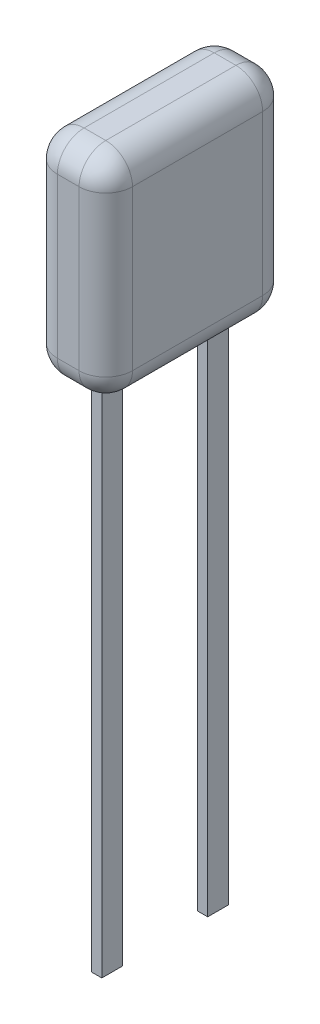
SolidWorks part; units mm, degrees
ref_plane "Front Plane" through (0, 0, 0) normal (0, 0, 1) x (1, 0, 0)
ref_plane "Top Plane" through (0, 0, 0) normal (0, 1, 0) x (1, 0, 0)
ref_plane "Right Plane" through (0, 0, 0) normal (1, 0, 0) x (0, 0, -1)
sketch "Sketch1" plane through (0, 0, 0) normal (1, 0, 0) x (0, 0, -1)
  line L1 (-1.56, 2.55) -> (1.56, 2.55)
  line L2 (-2.2, 1.91) -> (-2.2, -1.91)
  line L3 (-1.56, -2.55) -> (1.56, -2.55)
  line L4 (2.2, 1.91) -> (2.2, -1.91)
  line L5 (-2.2, 2.55) -> (2.2, -2.55) construction
  line L6 (-2.2, -2.55) -> (2.2, 2.55) construction
  arc A0 (-2.2, -1.91) -> (-1.56, -2.55) centre (-1.56, -1.91) ccw
  arc A1 (1.56, -2.55) -> (2.2, -1.91) centre (1.56, -1.91) ccw
  arc A2 (1.56, 2.55) -> (2.2, 1.91) centre (1.56, 1.91) cw
  arc A3 (-1.56, 2.55) -> (-2.2, 1.91) centre (-1.56, 1.91) ccw
  point P0 (0, 0)
  dimension "D3" = 0.64
  dimension "D1" = 4.4
  dimension "D2" = 5.1
extrude "Boss-Extrude1" add sketch "Sketch1" along normal blind 1.8
fillet "Fillet1" radius 0.64 16 edges at (1.8, 2.3625, -2.0125) (1.8, 0, -2.2) (1.8, -2.3625, -2.0125) (1.8, -2.55, 0) (1.8, -2.3625, 2.0125) (1.8, 0, 2.2) (1.8, 2.3625, 2.0125) (0, 2.3625, -2.0125) (0, 0, -2.2) (0, -2.3625, -2.0125) (0, -2.55, 0) (0, -2.3625, 2.0125) (0, 0, 2.2) (0, 2.3625, 2.0125) (1.8, 2.55, 0) (0, 2.55, 0)
ref_plane "Plane1" through (0.9, 0, 0) normal (1, 0, 0) x (0, 0, -1)
sketch "Sketch2" plane through (0.9, 0, 0) normal (1, 0, 0) x (0, 0, -1)
  line L0 (0, 0) -> (0, -3.8385) construction
  line L1 (0, -3.8385) -> (0, -10.741) construction
  line L2 (0, -10.741) -> (-1.2695, -10.741) construction
  line L3 (-1.2695, -10.741) -> (-1.2695, -10.3439) construction
  line L4 (1.0191, -14.926) -> (1.5199, -14.926)
  line L5 (-1.0191, -2.2634) -> (-0.3535, -1.9984)
  line L6 (-0.3535, -1.9984) -> (-0.3535, -1.5016)
  line L7 (-0.3535, -1.5016) -> (-1.5199, -1.5016)
  line L8 (-1.5199, -1.5016) -> (-1.5199, -10.3439)
  line L9 (-1.0191, -2.2634) -> (-1.0191, -14.926)
  line L10 (-1.0191, -14.926) -> (-1.5199, -14.926)
  line L11 (-1.5199, -14.926) -> (-1.5199, -10.3439)
  line L12 (1.5199, -14.926) -> (1.5199, -10.3439)
  line L13 (1.0191, -2.2634) -> (1.0191, -14.926)
  line L14 (1.5199, -1.5016) -> (1.5199, -10.3439)
  line L15 (1.5199, -1.5016) -> (1.5199, 1.91)
  line L16 (1.5199, 1.91) -> (-1.56, 1.91)
  line L17 (-1.56, 1.91) -> (-1.56, -1.3414)
  line L18 (-1.56, 1.91) -> (-1.56, -1.91) construction
  line L19 (-1.56, -1.3414) -> (0.4386, -1.3414)
  line L20 (0.4386, -1.3414) -> (1.0191, -2.2634)
  line L21 (1.56, 1.91) -> (-1.56, 1.91) construction
  circle A0 centre (1.0794, -1.5817) radius 0.2217
  circle A1 centre (-1.0191, -1.8576) radius 0.2281
extrude "Boss-Extrude2" add sketch "Sketch2" along normal blind 0.125 and the other way blind 0.125 separate body
